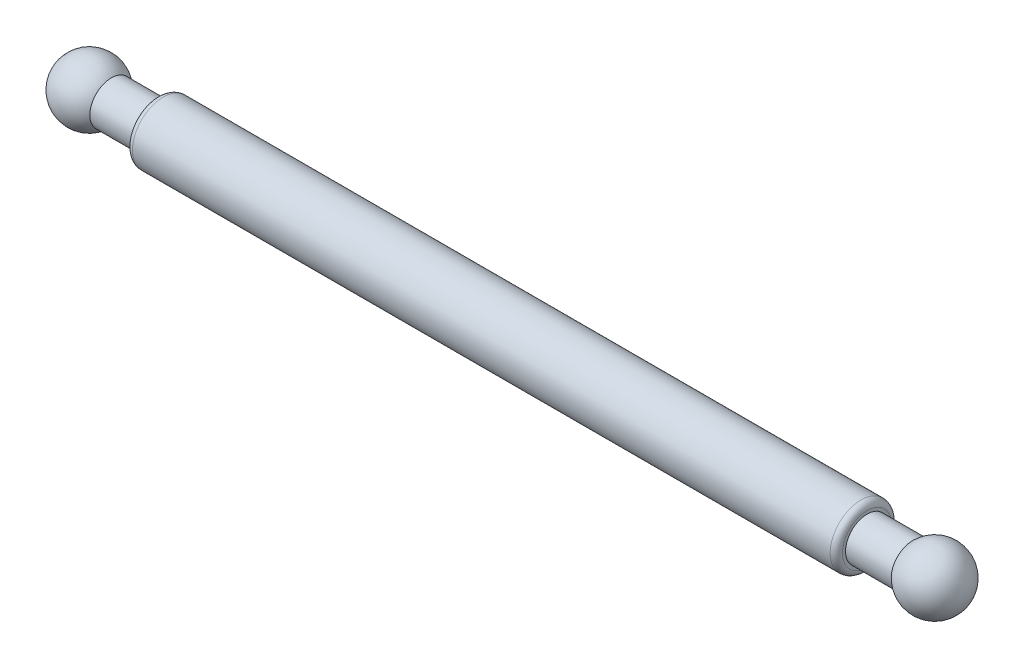
SolidWorks part; units mm, degrees
ref_plane "Front Plane" through (0, 0, 0) normal (0, 0, 1) x (1, 0, 0)
ref_plane "Top Plane" through (0, 0, 0) normal (0, 1, 0) x (1, 0, 0)
ref_plane "Right Plane" through (0, 0, 0) normal (1, 0, 0) x (0, 0, -1)
sketch "Sketch1" plane through (0, 0, 0) normal (0, 1, 0) x (1, 0, 0)
  line L0 (0, 5) -> (0, -5)
  arc A0 (0, -5) -> (0, 5) centre (0, 0) ccw
  dimension "D1" = 10
revolve "Revolve1" add sketch "Sketch1" angle 360 about L0
sketch "Sketch2" plane through (0, 0, 0) normal (1, 0, 0) x (0, 0, -1)
  circle A0 centre (0, 0) radius 3.5
  dimension "D1" = 7
extrude "Boss-Extrude1" add sketch "Sketch2" along normal blind 68.75
sketch "Sketch3" plane through (68.75, 0, 0) normal (1, 0, 0) x (0, 0, -1)
  circle A0 centre (0, 0) radius 5
  dimension "D1" = 10
extrude "Boss-Extrude2" add sketch "Sketch3" against normal blind 57.75
fillet "Fillet1" radius 1 1 edges at (11, 0, -5)
mirror "Mirror1" of bodies 103
